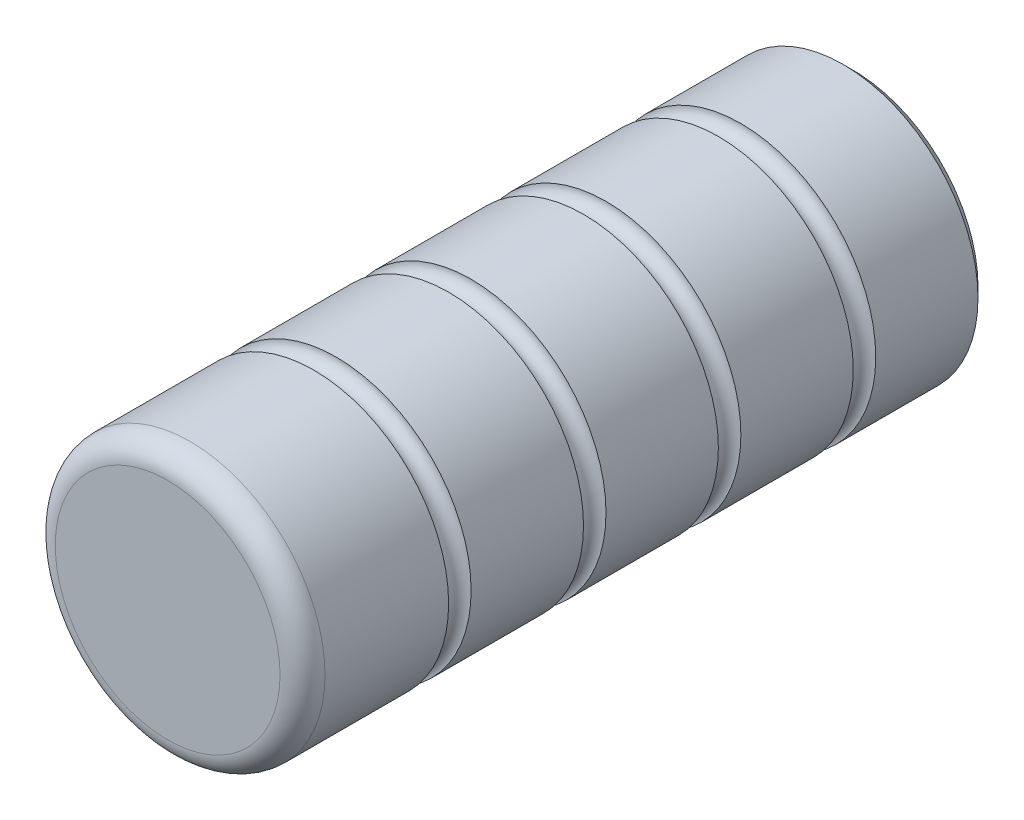
SolidWorks part; units mm, degrees
material "Latão"
ref_plane "Plano frontal" through (0, 0, 0) normal (0, 0, 1) x (1, 0, 0)
ref_plane "Plano superior" through (0, 0, 0) normal (0, 1, 0) x (1, 0, 0)
ref_plane "Plano direito" through (0, 0, 0) normal (1, 0, 0) x (0, 0, -1)
sketch "Esboço1" plane through (0, 0, 0) normal (0, 0, 1) x (1, 0, 0)
  circle A0 centre (0, 0) radius 6
  dimension "D1" = 12
extrude "Ressalto-extrusão1" add sketch "Esboço1" along normal blind 30.5
sketch "Esboço2" plane through (0, 0, 0) normal (0, 0, -1) x (-1, 0, 0)
  circle A0 centre (0, 0) radius 3.175
  dimension "D1" = 6.35
extrude "Corte-extrusão1" cut sketch "Esboço2" against normal blind 10
fillet "Filete1" radius 1 1 edges at (6, 0, 30.5)
sketch "Esboço3" plane through (0, 0, 0) normal (0, 1, 0) x (1, 0, 0)
  line L0 (-5, -30.5) -> (5, -30.5) construction
  line L1 (0, 0) -> (0, -31.5851) construction
  circle A0 centre (-6, -23.5) radius 0.5
  circle A1 centre (-6, -17.5) radius 0.5
  circle A2 centre (-6, -5.5) radius 0.5
  circle A3 centre (-6, -11.5) radius 0.5
  dimension "D1" = 1
  dimension "D2" = 7
  dimension "D3" = 6
  dimension "D4" = 6
  dimension "D5" = 6
  dimension "D6" = 6
  dimension "D7" = 6
  dimension "D8" = 6
  dimension "D9" = 6
revolve "Corte-Revolução1" cut sketch "Esboço3" angle 360 about L1
chamfer "Chanfro1" distance 0.45 angle 45 1 edges at (6, 0, 0)
